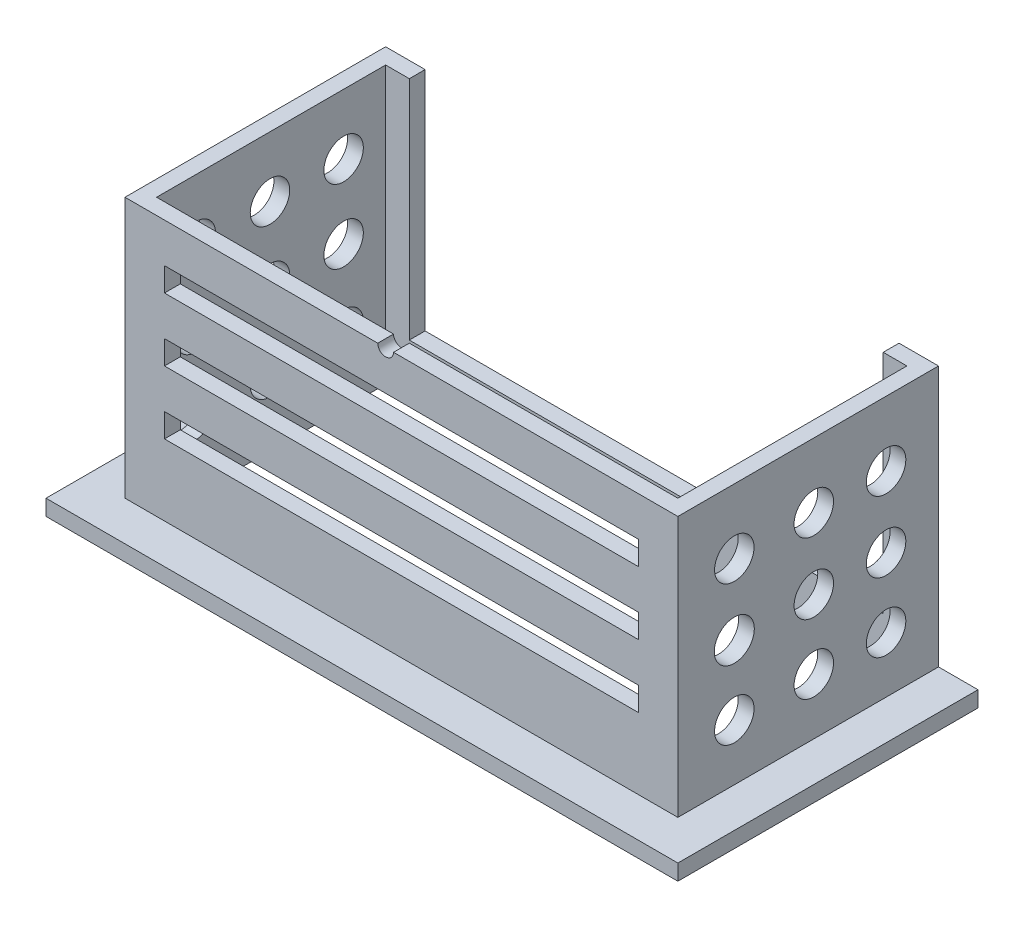
SolidWorks part; units mm, degrees
ref_plane "Front Plane" through (0, 0, 0) normal (0, 0, 1) x (1, 0, 0)
ref_plane "Top Plane" through (0, 0, 0) normal (0, 1, 0) x (1, 0, 0)
ref_plane "Right Plane" through (0, 0, 0) normal (1, 0, 0) x (0, 0, -1)
sketch "Sketch1" plane through (0, 0, 0) normal (0, 1, 0) x (1, 0, 0)
  line L0 (-61.1522, 39.7881) -> (-61.1522, 6.7881)
  line L1 (-61.1522, 6.7881) -> (8.8478, 6.7881)
  line L2 (8.8478, 6.7881) -> (8.8478, 39.7881)
  line L3 (8.8478, 39.7881) -> (-61.1522, 39.7881)
  dimension "D1" = 70
  dimension "D2" = 33
extrude "Boss-Extrude1" add sketch "Sketch1" along normal blind 35
sketch "Sketch2" plane through (8.8478, 0, 0) normal (1, 0, 0) x (0, 0, -1)
  line L0 (6.7881, 0) -> (39.7881, 0)
  line L1 (39.7881, 0) -> (39.7881, 2)
  line L2 (39.7881, 35) -> (39.7881, 0) construction
  line L3 (39.7881, 2) -> (6.7881, 2)
  line L4 (6.7881, 35) -> (6.7881, 0) construction
  line L5 (6.7881, 2) -> (6.7881, 0)
  dimension "D1" = 2
extrude "Boss-Extrude2" add sketch "Sketch2" along normal blind 5
sketch "Sketch3" plane through (0, 35, 0) normal (0, 1, 0) x (-1, 0, 0)
  line L0 (59.1522, -37.7881) -> (-6.8478, -37.7881)
  line L1 (-6.8478, -37.7881) -> (-6.8478, -8.7881)
  line L2 (-6.8478, -8.7881) -> (59.1522, -8.7881)
  line L3 (59.1522, -8.7881) -> (59.1522, -37.7881)
  line L4 (61.1522, -39.7881) -> (61.1522, -6.7881) construction
  line L5 (61.1522, -6.7881) -> (-8.8478, -6.7881) construction
  line L6 (-8.8478, -39.7881) -> (-8.8478, -6.7881) construction
  line L7 (-8.8478, -39.7881) -> (61.1522, -39.7881) construction
  dimension "D1" = 2
  dimension "D2" = 2
  dimension "D3" = 2
  dimension "D4" = 2
extrude "Cut-Extrude1" cut sketch "Sketch3" against normal through all contours L3 L2 L1 L0
sketch "Sketch9" plane through (0, 0, -6.7881) normal (0, 0, 1) x (1, 0, 0)
  line L1 (-61.1522, 35) -> (8.8478, 35) construction
  line L2 (-28.1522, 35) -> (-29.1522, 35)
  line L3 (-28.1522, 35) -> (-27.1522, 35)
  arc A0 (-29.1522, 35) -> (-27.1522, 35) centre (-28.1522, 35) ccw
  line M5 (8.8478, 35) -> (-61.1522, 35)
  dimension "D2" = 33
  dimension "D3" = 1
  dimension "D4" = 1
extrude "Cut-Extrude3" cut sketch "Sketch9" against normal blind 5 contours A0 M5
sketch "Sketch13" plane through (8.8478, 0, 0) normal (1, 0, 0) x (0, 0, -1)
  circle A0 centre (13.9338, 26.8035) radius 2.5
  circle A1 centre (13.9338, 17.8559) radius 2.5351
  circle A2 centre (13.9338, 9.1117) radius 2.5
  circle A3 centre (23.9999, 26.8035) radius 2.5
  circle A4 centre (23.9999, 17.8559) radius 2.5
  circle A5 centre (23.9999, 9.1117) radius 2.5
  circle A6 centre (33.1508, 9.1117) radius 2.5
  circle A7 centre (33.1508, 26.8035) radius 2.5
  circle A8 centre (33.1508, 17.8559) radius 2.5
  dimension "D1" = 5
  dimension "D2" = 5
  dimension "D3" = 5
  dimension "D4" = 5
  dimension "D5" = 5
  dimension "D6" = 5
  dimension "D7" = 5
  dimension "D8" = 5
extrude "Cut-Extrude4" cut sketch "Sketch13" against normal blind 5 contours A2 | A1 | A0 | A3 | A4 | A5 | A6 | A8 | A7
sketch "Sketch14" plane through (-61.1522, 0, 0) normal (-1, 0, 0) x (0, 0, 1)
  line L0 (-39.7881, 0) -> (-6.7881, 0)
  line L1 (-6.7881, 0) -> (-6.7881, 2)
  line L2 (-6.7881, 35) -> (-6.7881, 0) construction
  line L3 (-6.7881, 2) -> (-39.7881, 2)
  line L4 (-39.7881, 35) -> (-39.7881, 0) construction
  line L5 (-39.7881, 2) -> (-39.7881, 0)
  dimension "D1" = 2
extrude "Boss-Extrude4" add sketch "Sketch14" along normal blind 5
sketch "Sketch15" plane through (-61.1522, 0, 0) normal (-1, 0, 0) x (0, 0, 1)
  circle A0 centre (-32.4673, 27.35) radius 2.5
  circle A1 centre (-32.4673, 18.0296) radius 2.5
  circle A2 centre (-32.4673, 8.3561) radius 2.5
  circle A3 centre (-23.1469, 8.4267) radius 2.5
  circle A4 centre (-23.1469, 18.0296) radius 2.5
  circle A5 centre (-23.1469, 27.35) radius 2.5
  circle A6 centre (-13.7559, 27.35) radius 2.5
  circle A7 centre (-13.7559, 8.4267) radius 2.5
  circle A8 centre (-13.7559, 18.0296) radius 2.5
  dimension "D1" = 5
  dimension "D2" = 5
  dimension "D3" = 5
  dimension "D4" = 5
  dimension "D5" = 5
  dimension "D6" = 5
  dimension "D7" = 5
  dimension "D8" = 5
  dimension "D9" = 5
extrude "Cut-Extrude5" cut sketch "Sketch15" against normal blind 5 contours A2 | A3 | A7 | A8 | A4 | A1 | A0 | A5 | A6
sketch "Sketch16" plane through (0, 0, -39.7881) normal (0, 0, -1) x (-1, 0, 0)
  line L0 (-13.8478, 2) -> (66.1522, 2)
  line L1 (66.1522, 2) -> (66.1522, 0)
  line L2 (66.1522, 0) -> (-13.8478, 0)
  line L3 (-13.8478, 0) -> (66.1522, 0) construction
  line L4 (-13.8478, 0) -> (-13.8478, 2) construction
  line L5 (-13.8478, 0) -> (-13.8478, 2)
sketch "Sketch17" plane through (0, 0, -6.7881) normal (0, 0, 1) x (1, 0, 0)
  line L0 (-66.1522, 2) -> (-66.1522, 0)
  line L1 (-66.1522, 0) -> (13.8478, 0)
  line L2 (13.8478, 0) -> (13.8478, 2)
  line L3 (-66.1522, 2) -> (13.8478, 2)
extrude "Boss-Extrude6" add sketch "Sketch17" along normal blind 5
sketch "Sketch19" plane through (0, 0, -39.7881) normal (0, 0, -1) x (-1, 0, 0)
  line L0 (-3.8478, 35) -> (-3.8478, 6.3383)
  line L1 (-8.8478, 35) -> (61.1522, 35) construction
  line L2 (-3.8478, 6.3383) -> (56.1522, 6.3383)
  line L3 (56.1522, 6.3383) -> (56.1522, 35)
  line L4 (56.1522, 35) -> (-3.8478, 35)
  line L5 (-8.8478, 35) -> (-8.8478, 2) construction
  line M9 (61.1522, 35) -> (-8.8478, 35)
  dimension "D1" = 60
  dimension "D2" = 5
extrude "Cut-Extrude6" cut sketch "Sketch19" against normal blind 5 contours L2 L3 L0 M9
sketch "Sketch20" plane through (0, 0, -6.7881) normal (0, 0, 1) x (1, 0, 0)
  line L0 (-56.1522, 30) -> (3.8478, 30)
  line L1 (3.8478, 30) -> (3.8478, 27)
  line L2 (3.8478, 27) -> (-56.1522, 27)
  line L3 (-56.1522, 27) -> (-56.1522, 30)
  line L4 (-61.1522, 35) -> (-61.1522, 2) construction
  line L5 (-61.1522, 35) -> (-29.1522, 35) construction
  dimension "D1" = 60
  dimension "D2" = 3
  dimension "D3" = 5
  dimension "D4" = 5
sketch "Sketch21" plane through (0, 0, -6.7881) normal (0, 0, 1) x (1, 0, 0)
  line L0 (-56.1522, 22) -> (3.8478, 22)
  line L1 (3.8478, 22) -> (3.8478, 19)
  line L2 (3.8478, 19) -> (-56.1522, 19)
  line L3 (-56.1522, 19) -> (-56.1522, 22)
  line L4 (3.8478, 27) -> (-56.1522, 27) construction
  line L5 (8.8478, 35) -> (8.8478, 2) construction
  line L6 (-56.1522, 14) -> (3.8478, 14)
  line L7 (3.8478, 14) -> (3.8478, 11)
  line L8 (3.8478, 11) -> (-56.1522, 11)
  line L9 (-56.1522, 11) -> (-56.1522, 14)
  dimension "D1" = 3
  dimension "D2" = 60
  dimension "D3" = 5
  dimension "D4" = 5
  dimension "D5" = 60
  dimension "D6" = 3
  dimension "D7" = 5
  dimension "D8" = 5
extrude "Cut-Extrude7" cut sketch "Sketch20" against normal blind 5 contours L0 L1 L2 L3
extrude "Cut-Extrude8" cut sketch "Sketch21" against normal blind 5 contours L9 L8 L7 L6 | L2 L3 L0 L1
